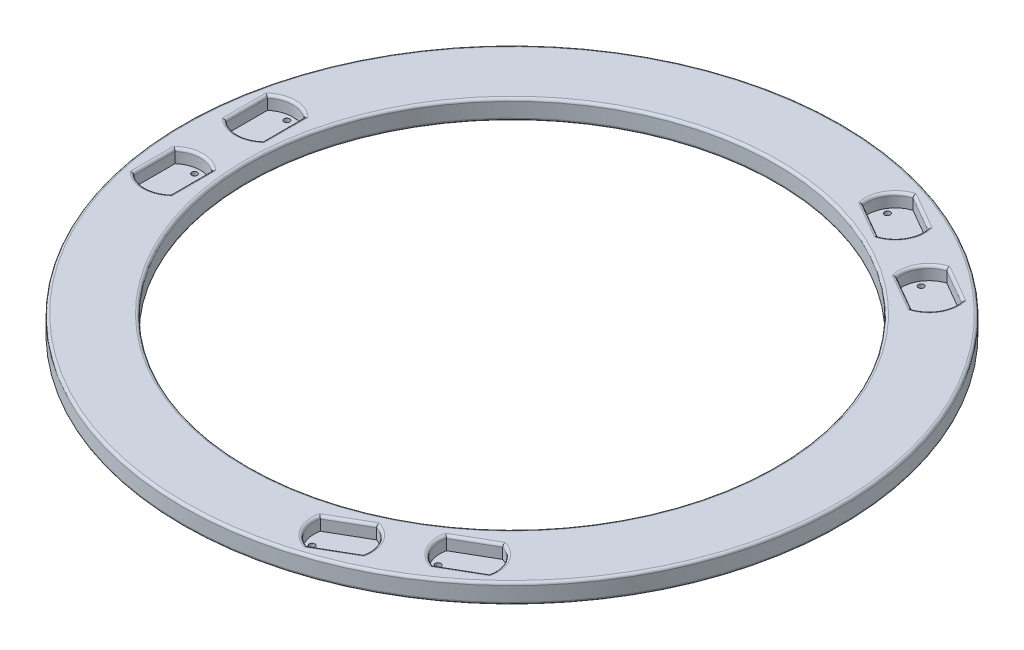
SolidWorks part; units mm, degrees
ref_plane "Front Plane" through (0, 0, 0) normal (0, 0, 1) x (1, 0, 0)
ref_plane "Top Plane" through (0, 0, 0) normal (0, 1, 0) x (1, 0, 0)
ref_plane "Right Plane" through (0, 0, 0) normal (1, 0, 0) x (0, 0, -1)
sketch "Sketch1" plane through (0, 0, 0) normal (0, 1, 0) x (1, 0, 0)
  circle A0 centre (0, 0) radius 250
  circle A5 centre (0, 0) radius 200
  point P8 (0.5393, -0.562)
  point P11 (0, 0)
  dimension "D1" = 400
  dimension "D2" = 500
extrude "Boss-Extrude1" add sketch "Sketch1" along normal blind 15
sketch "Sketch2" plane through (0, 15, 0) normal (0, 1, 0) x (1, 0, 0)
  line L0 (-125, -216.5064) -> (125, 216.5064) construction
  line L1 (250, 0) -> (-250, 0) construction
  line L2 (-125, 216.5064) -> (125, -216.5064) construction
  line L3 (74.2678, 229.9355) -> (101.3743, 214.2855)
  line L4 (60.2635, 205.6893) -> (87.3786, 190.0343)
  line L5 (134.8895, 194.9355) -> (161.9961, 179.2855)
  line L6 (120.8852, 170.6893) -> (148.0004, 155.0343)
  line L7 (161.9961, -179.2855) -> (134.8895, -194.9355)
  line L8 (148.0004, -155.0343) -> (120.8852, -170.6893)
  line L9 (87.3786, -190.0343) -> (60.2635, -205.6893)
  line L10 (101.3743, -214.2855) -> (74.2678, -229.9355)
  line L11 (-236.2639, -50.65) -> (-236.2639, -19.35)
  line L12 (-208.2639, -50.655) -> (-208.2639, -19.345)
  line L13 (-208.2639, 19.345) -> (-208.2639, 50.655)
  line L14 (-236.2639, 19.35) -> (-236.2639, 50.65)
  arc A0 (120.8852, -170.6893) -> (134.8895, -194.9355) centre (141.4414, -174.9838) ccw
  circle A1 centre (0, 0) radius 250 construction
  arc A2 (148.0004, 155.0343) -> (161.9961, 179.2855) centre (141.4414, 174.9838) ccw
  arc A3 (74.2678, 229.9355) -> (60.2635, 205.6893) centre (80.8197, 209.9838) ccw
  circle A4 centre (0, 0) radius 200 construction
  arc A5 (101.3743, -214.2855) -> (87.3786, -190.0343) centre (80.8197, -209.9838) ccw
  arc A6 (-208.2639, -19.345) -> (-236.2639, -19.35) centre (-222.2611, -35) ccw
  arc A7 (-208.2639, 50.655) -> (-236.2639, 50.65) centre (-222.2611, 35) ccw
  arc A8 (87.3786, 190.0343) -> (101.3743, 214.2855) centre (80.8197, 209.9838) ccw
  arc A9 (134.8895, 194.9355) -> (120.8852, 170.6893) centre (141.4414, 174.9838) ccw
  arc A10 (161.9961, -179.2855) -> (148.0004, -155.0343) centre (141.4414, -174.9838) ccw
  arc A11 (60.2635, -205.6893) -> (74.2678, -229.9355) centre (80.8197, -209.9838) ccw
  arc A12 (-236.2639, -50.65) -> (-208.2639, -50.655) centre (-222.2611, -35) ccw
  arc A13 (-236.2639, 19.35) -> (-208.2639, 19.345) centre (-222.2611, 35) ccw
  point P11 (0, 0)
  point P26 (0, 0)
  point P51 (0, 0)
  dimension "D2" = 42
  dimension "D3" = 35
  dimension "D4" = 225
  dimension "D5" = 28
  dimension "D6" = 31.3
  dimension "D1" = 3
  dimension "D7" = 3
  dimension "D8" = 3
extrude "Cut-Extrude1" cut sketch "Sketch2" against normal blind 10
fillet "Fillet1" radius 2 28 edges at (0, 0, 200) (0, 0, 250) (0, 15, 200) (0, 15, 250) (159.6298, 15, -164.487) (62.635, 15, -220.487) (99.0081, 15, 199.487) (123.2568, 15, 185.487) (-222.2648, 15, -56) (-222.2648, 15, 14) (73.821, 15, -197.8618) (99.0081, 15, -199.487) (87.821, 15, -222.1105) (134.4428, 15, -162.8618) (148.4428, 15, -187.1105) (123.2568, 15, -185.487) (134.4428, 15, 162.8618) (148.4428, 15, 187.1105) (159.6298, 15, 164.487) (73.821, 15, 197.8618) (62.635, 15, 220.487) (87.821, 15, 222.1105) (-208.2639, 15, 35) (-236.2639, 15, 35) (-222.2648, 15, 56) (-208.2639, 15, -35) (-236.2639, 15, -35) (-222.2648, 15, -14)
hole_wizard "M4 Clearance Hole1" positions "Sketch4" profile "Sketch3" hole size "M4" standard "ISO" end condition through all
sketch "Sketch4" plane through (0, 5, 0) normal (0, 1, 0) x (1, 0, 0)
  line L1 (-222.2648, -14) -> (-222.2648, -56) construction
  line L4 (-222.2648, 14) -> (-222.2648, 56) construction
  line L6 (99.0081, -199.487) -> (62.635, -220.487) construction
  line L8 (123.2568, -185.487) -> (159.6298, -164.487) construction
  line L10 (159.6298, 164.487) -> (123.2568, 185.487) construction
  line L13 (62.635, 220.487) -> (99.0081, 199.487) construction
  line L15 (80.8215, 209.987) -> (77.1428, 203.6153) construction
  line L17 (141.4433, 174.987) -> (137.2631, 167.7466) construction
  line L19 (80.8215, -209.987) -> (75.3559, -200.5202) construction
  line L21 (141.4433, -174.987) -> (137.2631, -167.7466) construction
  line L23 (-222.2648, -35) -> (-215.5322, -35) construction
  line L25 (-222.2648, 35) -> (-216.1937, 35) construction
  arc A0 (-208.2639, -19.345) -> (-236.2639, -19.35) centre (-222.2611, -35) ccw construction
  arc A1 (-236.2639, -50.65) -> (-208.2639, -50.655) centre (-222.2611, -35) ccw construction
  arc A2 (-236.2639, 19.35) -> (-208.2639, 19.345) centre (-222.2611, 35) ccw construction
  arc A3 (-208.2639, 50.655) -> (-236.2639, 50.65) centre (-222.2611, 35) ccw construction
  arc A4 (101.3743, -214.2855) -> (87.3786, -190.0343) centre (80.8197, -209.9838) ccw construction
  arc A5 (60.2635, -205.6893) -> (74.2678, -229.9355) centre (80.8197, -209.9838) ccw construction
  arc A6 (120.8852, -170.6893) -> (134.8895, -194.9355) centre (141.4414, -174.9838) ccw construction
  arc A7 (161.9961, -179.2855) -> (148.0004, -155.0343) centre (141.4414, -174.9838) ccw construction
  arc A8 (148.0004, 155.0343) -> (161.9961, 179.2855) centre (141.4414, 174.9838) ccw construction
  arc A9 (134.8895, 194.9355) -> (120.8852, 170.6893) centre (141.4414, 174.9838) ccw construction
  arc A10 (74.2678, 229.9355) -> (60.2635, 205.6893) centre (80.8197, 209.9838) ccw construction
  arc A11 (87.3786, 190.0343) -> (101.3743, 214.2855) centre (80.8197, 209.9838) ccw construction
  point P0 (-222.2648, -18.5)
  point P2 (-222.2648, -51.5)
  point P4 (-222.2648, 51.5)
  point P6 (-222.2648, 18.5)
  point P8 (66.5321, 218.237)
  point P10 (95.1109, 201.737)
  point P12 (127.1539, 183.237)
  point P14 (155.7327, 166.737)
  point P16 (155.7327, -166.737)
  point P18 (127.1539, -183.237)
  point P20 (95.1109, -201.737)
  point P23 (66.5321, -218.237)
  dimension "D1" = 33
  dimension "D2" = 33
  dimension "D3" = 33
  dimension "D4" = 33
  dimension "D5" = 33
  dimension "D6" = 33
sketch "Sketch3" plane through (-222.2648, 5, 18.5) normal (1, 0, 0) x (0, 0, 1)
  line L0 (0, 0) -> (0, 5)
  line L1 (0, 5) -> (2.15, 5)
  line L2 (2.15, 5) -> (2.15, 0)
  line L5 (2.15, 0) -> (0, 0)
  line L11 (0, -6.35) -> (0, 107.95) construction
  dimension "Thru Hole Dia." = 4.3
  dimension "Thru Hole Depth" = 5
